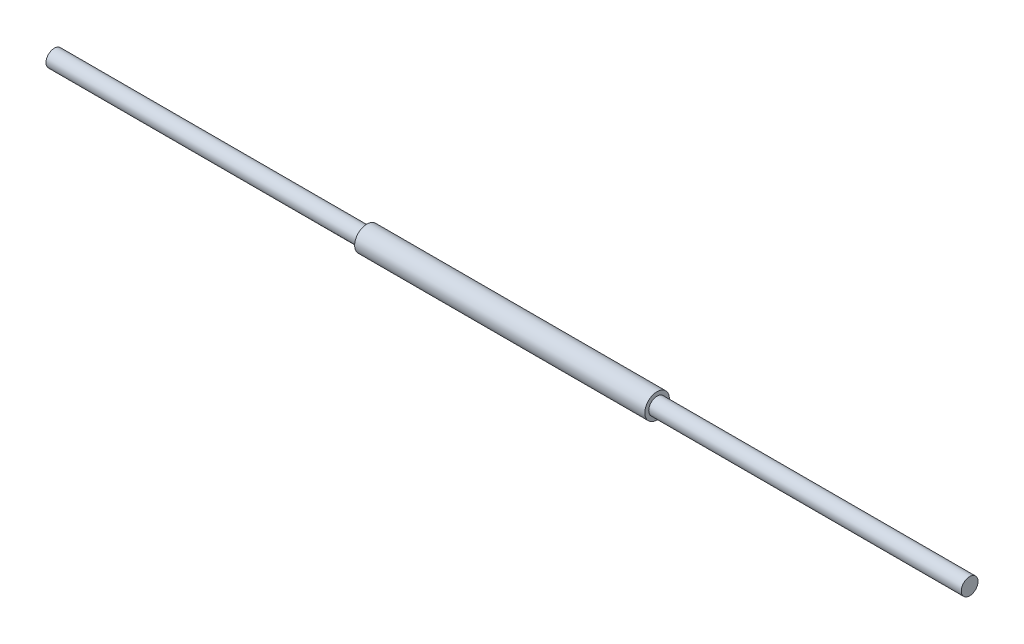
SolidWorks part; units mm, degrees
ref_plane "Front Plane" through (0, 0, 0) normal (0, 0, 1) x (1, 0, 0)
ref_plane "Top Plane" through (0, 0, 0) normal (0, 1, 0) x (1, 0, 0)
ref_plane "Right Plane" through (0, 0, 0) normal (1, 0, 0) x (0, 0, -1)
sketch "Sketch1" plane through (0, 0, 0) normal (0, 0, 1) x (1, 0, 0)
  line L0 (0, 0) -> (0, 6.8874) construction
  line L1 (-82.55, 3.4925) -> (82.55, 3.4925)
  line L2 (-82.55, 3.4925) -> (-82.55, -3.4925)
  line L3 (-82.55, -3.4925) -> (82.55, -3.4925)
  line L4 (82.55, 3.4925) -> (82.55, -3.4925)
  line L5 (-82.55, 3.4925) -> (82.55, -3.4925) construction
  line L6 (-82.55, -3.4925) -> (82.55, 3.4925) construction
  line L7 (-82.55, -3.4925) -> (-260.35, -3.4925)
  line L8 (-82.55, -3.4925) -> (-82.55, 1.27)
  line L9 (-82.55, 1.27) -> (-260.35, 1.27)
  line L10 (-260.35, -3.4925) -> (-260.35, 1.27)
  line L11 (260.35, -3.4925) -> (260.35, 1.27)
  line L12 (82.55, 1.27) -> (260.35, 1.27)
  line L13 (82.55, -3.4925) -> (260.35, -3.4925)
  point P0 (0, 0)
  point P14 (260.35, -1.1112)
  dimension "D1" = 6.985
  dimension "D2" = 165.1
  dimension "D3" = 4.7625
  dimension "D4" = 520.7
revolve "Revolve1" add sketch "Sketch1" angle 360 about L7
